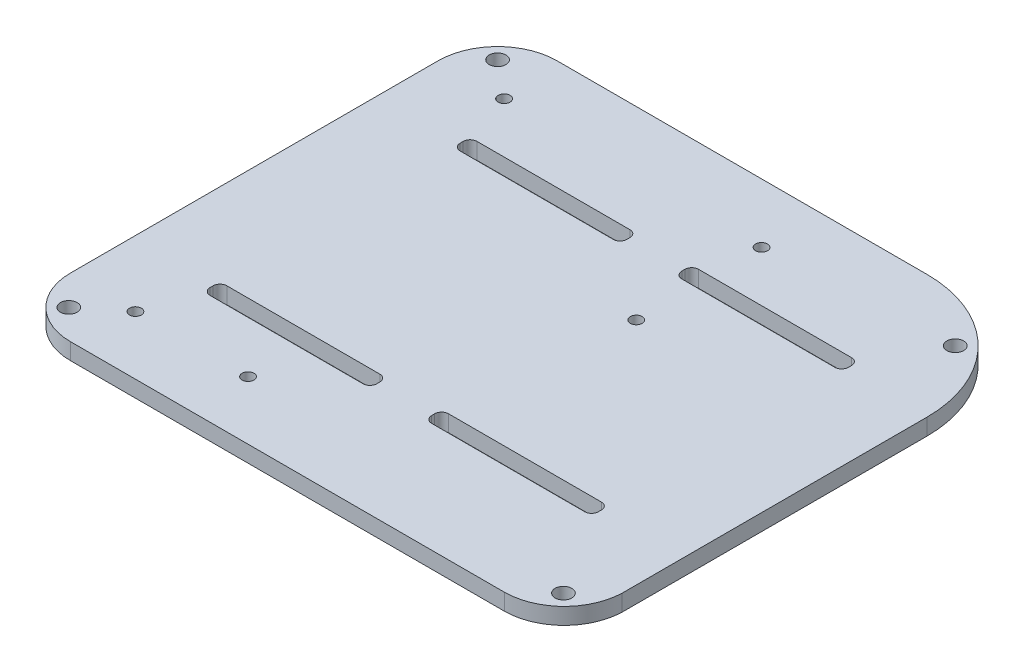
SolidWorks part; units mm, degrees
material "PMMA"
ref_plane "Front Plane" through (0, 0, 0) normal (0, 0, 1) x (1, 0, 0)
ref_plane "Top Plane" through (0, 0, 0) normal (0, 1, 0) x (1, 0, 0)
ref_plane "Right Plane" through (0, 0, 0) normal (1, 0, 0) x (0, 0, -1)
sketch "Sketch1" plane through (0, 0, 0) normal (0, 1, 0) x (1, 0, 0)
  line L1 (-51.2097, -0.298) -> (51.1203, -0.298) construction
  line L2 (-34.6997, 24.392) -> (-6.3947, 24.392)
  line L3 (-35.9697, 23.122) -> (-35.9697, 22.562)
  line L5 (-34.6997, 21.292) -> (-6.3947, 21.292)
  line L7 (35.8803, 23.122) -> (35.8803, 22.562)
  line L14 (35.8803, -23.718) -> (35.8803, -23.158)
  line L17 (-40.2097, 44.712) -> (28.2403, 44.712)
  line L18 (51.1203, 21.832) -> (51.1203, -34.5982)
  line L19 (-40.2097, -45.308) -> (40.1303, -45.308)
  line L20 (-51.2097, 33.712) -> (-51.2097, -34.308)
  line L22 (-42.3087, 35.8109) -> (-47.9879, 41.4901) construction
  line L23 (38.7844, 32.3761) -> (44.4189, 38.0106) construction
  line L24 (47.7767, -42.1608) -> (44.6195, -38.8846) construction
  line L25 (-47.9879, -42.0862) -> (-42.2863, -36.4294) construction
  line L26 (-5.1247, 23.122) -> (-5.1247, 22.562)
  line L27 (5.0353, 23.122) -> (5.0353, 22.562)
  line L28 (6.3053, 24.392) -> (34.6103, 24.392)
  line L29 (6.3053, 21.292) -> (34.6103, 21.292)
  line L30 (6.3053, -21.888) -> (34.6103, -21.888)
  line L31 (6.3053, -24.988) -> (34.6103, -24.988)
  line L32 (5.0353, -23.718) -> (5.0353, -23.158)
  line L33 (-5.1247, -23.718) -> (-5.1247, -23.158)
  line L34 (-34.6997, -21.888) -> (-6.3947, -21.888)
  line L35 (-35.9697, -23.718) -> (-35.9697, -23.158)
  line L36 (-34.6997, -24.988) -> (-6.3947, -24.988)
  arc A0 (-35.9697, 23.122) -> (-34.6997, 24.392) centre (-34.6997, 23.122) cw
  circle A1 centre (-39.0197, -34.478) radius 1.1
  circle A2 centre (-18.1797, -34.478) radius 1.1
  circle A3 centre (-39.0197, 33.732) radius 1.1
  circle A4 centre (8.6103, 33.7319) radius 1.1
  circle A5 centre (8.655, 10.512) radius 1.1
  arc A6 (-35.9697, 22.562) -> (-34.6997, 21.292) centre (-34.6997, 22.562) ccw
  arc A7 (35.8803, 23.122) -> (34.6103, 24.392) centre (34.6103, 23.122) ccw
  arc A9 (34.6103, 21.292) -> (35.8803, 22.562) centre (34.6103, 22.562) ccw
  arc A10 (-6.3947, 24.392) -> (-5.1247, 23.122) centre (-6.3947, 23.122) cw
  arc A11 (-5.1247, 22.562) -> (-6.3947, 21.292) centre (-6.3947, 22.562) cw
  arc A22 (51.1203, 21.832) -> (28.2403, 44.712) centre (28.2403, 21.832) ccw
  arc A23 (51.1203, -34.5982) -> (40.1303, -45.308) centre (40.0369, -34.2185) cw
  arc A24 (-51.2097, -34.308) -> (-40.2097, -45.308) centre (-40.2097, -34.308) ccw
  arc A25 (-40.2097, 44.712) -> (-51.2097, 33.712) centre (-40.2097, 33.712) ccw
  circle A28 centre (-45.8666, 39.3688) radius 1.55
  circle A29 centre (42.2975, 35.8892) radius 1.55
  circle A30 centre (45.695, -40.0007) radius 1.55
  circle A31 centre (-45.8583, -39.9733) radius 1.55
  arc A32 (5.0353, 22.562) -> (6.3053, 21.292) centre (6.3053, 22.562) ccw
  arc A33 (5.0353, 23.122) -> (6.3053, 24.392) centre (6.3053, 23.122) cw
  arc A34 (35.8803, -23.718) -> (34.6103, -24.988) centre (34.6103, -23.718) cw
  arc A35 (34.6103, -21.888) -> (35.8803, -23.158) centre (34.6103, -23.158) cw
  arc A36 (5.0353, -23.158) -> (6.3053, -21.888) centre (6.3053, -23.158) cw
  arc A37 (5.0353, -23.718) -> (6.3053, -24.988) centre (6.3053, -23.718) ccw
  arc A38 (-6.3947, -24.988) -> (-5.1247, -23.718) centre (-6.3947, -23.718) ccw
  arc A39 (-5.1247, -23.158) -> (-6.3947, -21.888) centre (-6.3947, -23.158) ccw
  arc A40 (-35.9697, -23.158) -> (-34.6997, -21.888) centre (-34.6997, -23.158) cw
  arc A41 (-35.9697, -23.718) -> (-34.6997, -24.988) centre (-34.6997, -23.718) ccw
  point P36 (43.165, -37.128)
  dimension "D4" = 2.2
  dimension "D22" = 21.59
  dimension "D41" = 3.1
  dimension "D43" = 3.1
  dimension "D45" = 3.1
  dimension "D47" = 3.1
  dimension "D14" = 1.27
  dimension "D15" = 1.27
  dimension "D16" = 1.27
  dimension "D17" = 1.27
  dimension "D18" = 1.27
  dimension "D19" = 1.27
  dimension "D20" = 1.27
  dimension "D21" = 1.27
  dimension "D2" = 10.83
  dimension "D3" = 20.84
  dimension "D5" = 12.19
  dimension "D6" = 12.19
  dimension "D7" = 10.98
  dimension "D8" = 15.24
  dimension "D9" = 47.63
  dimension "D10" = 23.22
  dimension "D11" = 15.24
  dimension "D12" = 3.1
  dimension "D13" = 20.32
  dimension "D40" = 3
  dimension "D42" = 3
  dimension "D44" = 3
  dimension "D46" = 3
extrude "Boss-Extrude1" add sketch "Sketch1" along normal blind 3.048
